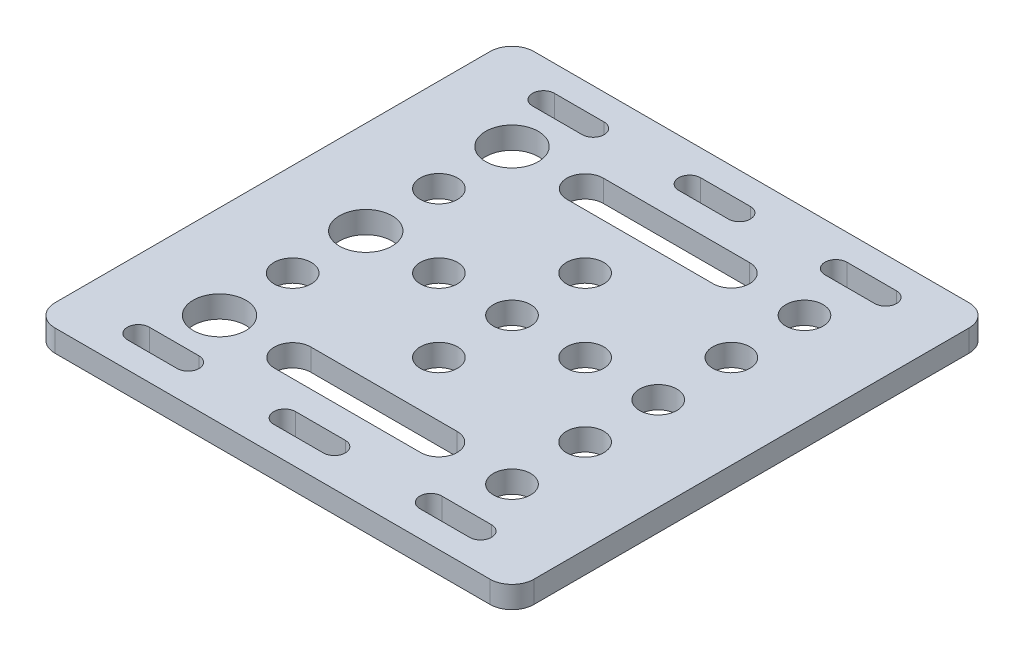
SolidWorks part; units mm, degrees
ref_plane "Front Plane" through (0, 0, 0) normal (0, 0, 1) x (1, 0, 0)
ref_plane "Top Plane" through (0, 0, 0) normal (0, 1, 0) x (1, 0, 0)
ref_plane "Right Plane" through (0, 0, 0) normal (1, 0, 0) x (0, 0, -1)
sketch "Sketch1" plane through (0, 0, 0) normal (0, 1, 0) x (1, 0, 0)
  line L1 (-29.75, 32.75) -> (29.75, 32.75)
  line L2 (-32.75, 29.75) -> (-32.75, -29.75)
  line L3 (-29.75, -32.75) -> (29.75, -32.75)
  line L4 (32.75, 29.75) -> (32.75, -29.75)
  line L5 (-32.75, 32.75) -> (32.75, -32.75) construction
  line L6 (-32.75, -32.75) -> (32.75, 32.75) construction
  arc A0 (29.75, -32.75) -> (32.75, -29.75) centre (29.75, -29.75) ccw
  arc A1 (-32.75, -29.75) -> (-29.75, -32.75) centre (-29.75, -29.75) ccw
  arc A2 (-29.75, 32.75) -> (-32.75, 29.75) centre (-29.75, 29.75) ccw
  arc A3 (29.75, 32.75) -> (32.75, 29.75) centre (29.75, 29.75) cw
  point P0 (0, 0)
  dimension "D2" = 3
  dimension "D1" = 65.5
extrude "Boss-Extrude1" add sketch "Sketch1" along normal blind 3
sketch "Sketch2" plane through (0, 3, 0) normal (0, 1, 0) x (1, 0, 0)
  line L0 (0, 0) -> (10, 0) construction
  line L1 (-20, -10) -> (0, -10) construction
  line L2 (-23.4, 29.2) -> (-16.6, 29.2)
  line L3 (-16.6, 26.2) -> (-23.4, 26.2)
  line L4 (-32.75, 29.75) -> (-32.75, -29.75) construction
  line L5 (29.75, 32.75) -> (-29.75, 32.75) construction
  line L6 (-3.4, 29.2) -> (3.4, 29.2)
  line L7 (3.4, 26.2) -> (-3.4, 26.2)
  line L8 (16.6, 29.2) -> (23.4, 29.2)
  line L9 (23.4, 26.2) -> (16.6, 26.2)
  line L10 (-3.4, -26.2) -> (3.4, -26.2)
  line L11 (3.4, -29.2) -> (-3.4, -29.2)
  line L12 (16.6, -26.2) -> (23.4, -26.2)
  line L13 (23.4, -29.2) -> (16.6, -29.2)
  line L14 (-23.4, -26.2) -> (-16.6, -26.2)
  line L15 (-16.6, -29.2) -> (-23.4, -29.2)
  line L16 (-23.4, 26.2) -> (-3.4, 26.2) construction
  line L17 (-10, 22.5) -> (10, 22.5)
  line L18 (10, 17.5) -> (-10, 17.5)
  line L19 (10, -17.5) -> (-10, -17.5)
  line L20 (-10, -22.5) -> (10, -22.5)
  circle A0 centre (0, 0) radius 2.55
  circle A2 centre (-20, -20) radius 3.6
  circle A3 centre (-20, -10) radius 2.55
  circle A4 centre (-20, 0) radius 3.6
  circle A5 centre (-20, 10) radius 2.55
  circle A6 centre (-20, 20) radius 3.6
  circle A7 centre (-10, 0) radius 2.55
  circle A8 centre (10, 0) radius 2.55
  circle A9 centre (20, 0) radius 2.55
  circle A10 centre (0, -10) radius 2.55
  circle A11 centre (0, 10) radius 2.55
  circle A12 centre (20, -10) radius 2.55
  circle A13 centre (20, 10) radius 2.55
  circle A14 centre (20, 20) radius 2.55
  circle A15 centre (20, -20) radius 2.55
  arc A16 (-16.6, 29.2) -> (-16.6, 26.2) centre (-16.6, 27.7) cw
  arc A17 (-23.4, 26.2) -> (-23.4, 29.2) centre (-23.4, 27.7) cw
  arc A18 (-3.4, 26.2) -> (-3.4, 29.2) centre (-3.4, 27.7) cw
  arc A19 (3.4, 29.2) -> (3.4, 26.2) centre (3.4, 27.7) cw
  arc A20 (16.6, 26.2) -> (16.6, 29.2) centre (16.6, 27.7) cw
  arc A21 (23.4, 29.2) -> (23.4, 26.2) centre (23.4, 27.7) cw
  arc A22 (-3.4, -29.2) -> (-3.4, -26.2) centre (-3.4, -27.7) cw
  arc A23 (3.4, -26.2) -> (3.4, -29.2) centre (3.4, -27.7) cw
  arc A24 (16.6, -29.2) -> (16.6, -26.2) centre (16.6, -27.7) cw
  arc A25 (23.4, -26.2) -> (23.4, -29.2) centre (23.4, -27.7) cw
  arc A26 (-23.4, -29.2) -> (-23.4, -26.2) centre (-23.4, -27.7) cw
  arc A27 (-16.6, -26.2) -> (-16.6, -29.2) centre (-16.6, -27.7) cw
  arc A28 (10, 22.5) -> (10, 17.5) centre (10, 20) cw
  arc A29 (-10, 17.5) -> (-10, 22.5) centre (-10, 20) cw
  arc A30 (10, -22.5) -> (10, -17.5) centre (10, -20) ccw
  arc A31 (-10, -17.5) -> (-10, -22.5) centre (-10, -20) ccw
  point P41 (-20, 29.2)
  point P84 (0, 17.5)
  point P85 (0, 0)
  point P86 (0, 0)
  point P87 (-7.7971, 17.5)
  point P88 (0, 0)
  point P89 (0, 0)
  dimension "D1" = 10
  dimension "D3" = 7.2
  dimension "D4" = 5.1
  dimension "D2" = 3
  dimension "D5" = 10
  dimension "D6" = 20
  dimension "D7" = 10
  dimension "D8" = 10
  dimension "D9" = 9.35
  dimension "D10" = 5.05
  dimension "D11" = 3
  dimension "D13" = 20
  dimension "D14" = 5
  dimension "D12" = 2
extrude "Cut-Extrude1" cut sketch "Sketch2" against normal through all
